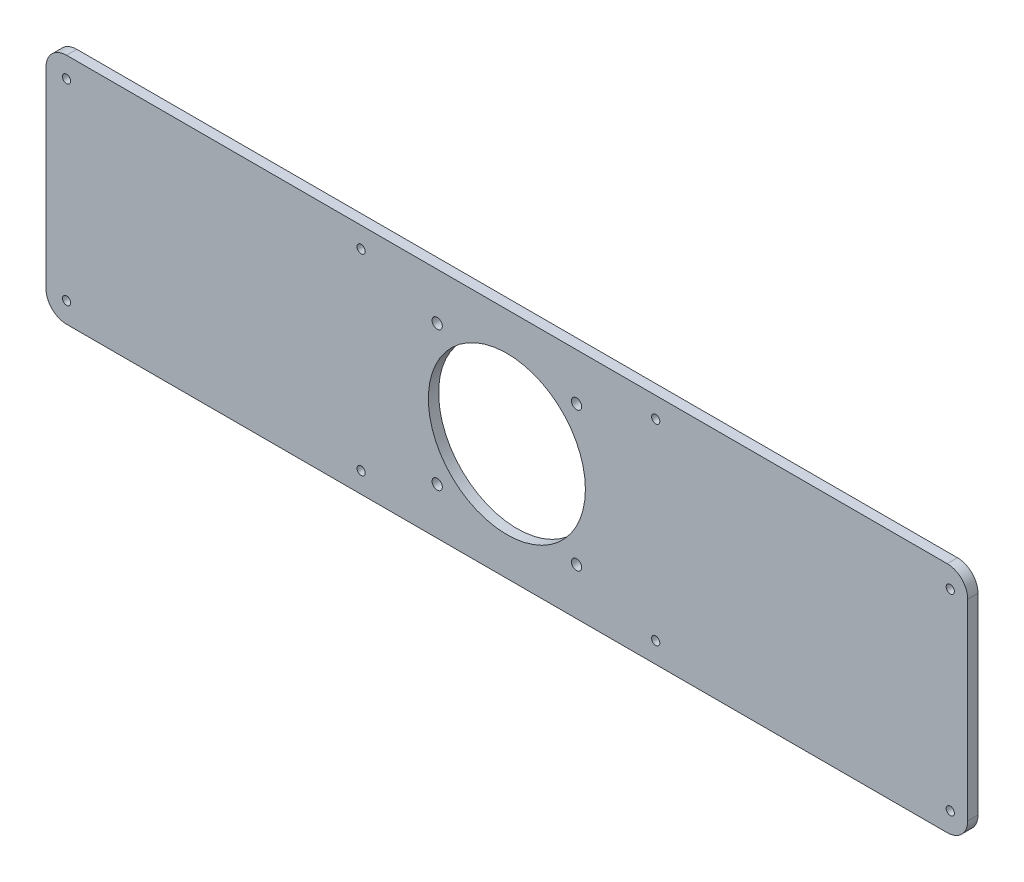
SolidWorks part; units mm, degrees
ref_plane "Plan de face" through (0, 0, 0) normal (0, 0, 1) x (1, 0, 0)
ref_plane "Plan de dessus" through (0, 0, 0) normal (0, 1, 0) x (1, 0, 0)
ref_plane "Plan de droite" through (0, 0, 0) normal (1, 0, 0) x (0, 0, -1)
sketch "Esquisse1" plane through (0, 0, 0) normal (0, 0, 1) x (1, 0, 0)
  line L0 (10, 103.5) -> (10, 10) construction
  line L1 (0, 0) -> (449, 0)
  line L2 (0, 0) -> (0, 113.5)
  line L3 (0, 113.5) -> (449, 113.5)
  line L4 (449, 0) -> (449, 113.5)
  line L5 (224.5, 113.5) -> (224.5, 0) construction
  line L6 (224.5, 56.75) -> (258.4411, 90.6911) construction
  line L7 (224.5, 56.75) -> (272.5, 56.75) construction
  circle A0 centre (10, 10) radius 2
  circle A1 centre (153.5, 10) radius 2
  circle A2 centre (297, 10) radius 2
  circle A3 centre (440.5, 10) radius 2
  circle A4 centre (153.5, 103.5) radius 2
  circle A5 centre (297, 103.5) radius 2
  circle A6 centre (440.5, 103.5) radius 2
  circle A7 centre (10, 103.5) radius 2
  circle A8 centre (224.5, 56.75) radius 38.25
  circle A9 centre (224.5, 56.75) radius 48 construction
  circle A10 centre (258.4411, 90.6911) radius 2.5
  circle A11 centre (258.4411, 22.8089) radius 2.5
  circle A12 centre (190.5589, 22.8089) radius 2.5
  circle A13 centre (190.5589, 90.6911) radius 2.5
  point P28 (180.6973, 97.8556)
  point P30 (224.5, 56.75)
  point P38 (224.5, 56.75)
  dimension "D1" = 4
  dimension "D10" = 96
  dimension "D11" = 76.5
  dimension "D13" = 5
  dimension "D2" = 449
  dimension "D3" = 113.5
  dimension "D6" = 10
  dimension "D7" = 10
  dimension "D8" = 143.5
  dimension "D9" = 93.5
  dimension "D12" = 45
  dimension "D15" = 430.5
  dimension "D4" = 4
  dimension "D5" = 2
  dimension "D14" = 4
extrude "Boss.-Extru.1" add sketch "Esquisse1" along normal blind 5
fillet "Congé1" radius 10 4 edges at (0, 0, 2.5) (0, 113.5, 2.5) (449, 0, 2.5) (449, 113.5, 2.5)
